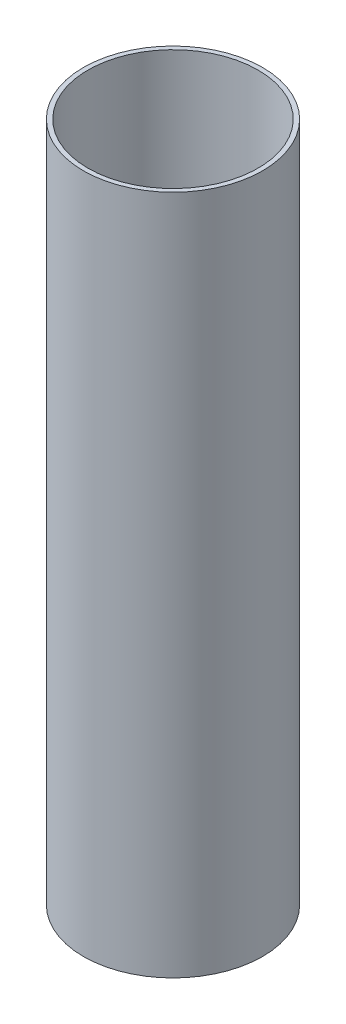
SolidWorks part; units mm, degrees
ref_plane "Front Plane" through (0, 0, 0) normal (0, 0, 1) x (1, 0, 0)
ref_plane "Top Plane" through (0, 0, 0) normal (0, 1, 0) x (1, 0, 0)
ref_plane "Right Plane" through (0, 0, 0) normal (1, 0, 0) x (0, 0, -1)
sketch "Sketch1" plane through (0, 0, 0) normal (0, 1, 0) x (1, 0, 0)
  circle A0 centre (0, 0) radius 31.25
  circle A1 centre (0, 0) radius 32.9
  dimension "D1" = 65.8
  dimension "D2" = 62.5
extrude "Boss-Extrude1" add sketch "Sketch1" along normal mid plane 250
